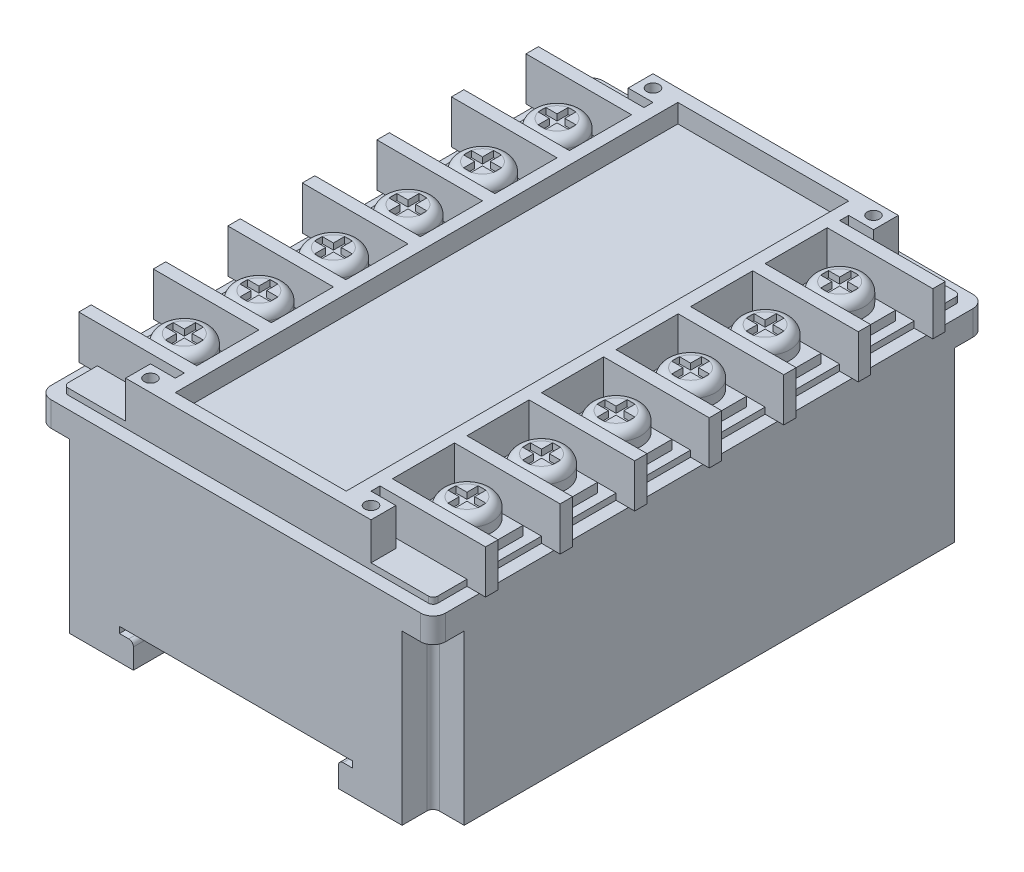
SolidWorks part; units mm, degrees
ref_plane "Front Plane" through (0, 0, 0) normal (0, 0, 1) x (1, 0, 0)
ref_plane "Top Plane" through (0, 0, 0) normal (0, 1, 0) x (1, 0, 0)
ref_plane "Right Plane" through (0, 0, 0) normal (1, 0, 0) x (0, 0, -1)
sketch "din rail profile sketch" plane through (0, 0, 0) normal (0, 0, 1) x (1, 0, 0)
  line L0 (0, 0) -> (1.75, 0)
  line L1 (2.25, -0.5) -> (2.25, -7)
  line L2 (3.25, -8) -> (34.25, -8)
  line L3 (18.75, -5.5) -> (18.75, 6.0393) construction
  line L4 (35.25, -0.5) -> (35.25, -7)
  line L5 (37.5, 0) -> (35.75, 0)
  line L6 (0, 1) -> (2.25, 1)
  line L7 (3.25, 0) -> (3.25, -6.8)
  line L8 (3.45, -7) -> (34.05, -7)
  line L9 (34.25, 0) -> (34.25, -6.8)
  line L10 (37.5, 1) -> (35.25, 1)
  line L11 (37.5, 1) -> (37.5, 0)
  line L12 (0, 0) -> (0, 1)
  line L13 (3.25, -7) -> (34.25, -7) construction
  line L14 (3.25, 1) -> (3.25, -7) construction
  line L15 (34.25, 1) -> (34.25, -7) construction
  line L16 (37.5, 0) -> (35.25, 0) construction
  line L17 (35.25, 0) -> (35.25, -8) construction
  line L18 (0, 0) -> (2.25, 0) construction
  line L19 (2.25, 0) -> (2.25, -8) construction
  line L20 (2.25, -8) -> (35.25, -8) construction
  line L21 (37.5, 1) -> (34.25, 1) construction
  line L22 (0, 1) -> (3.25, 1) construction
  arc A0 (3.45, -7) -> (3.25, -6.8) centre (3.45, -6.8) cw
  arc A1 (34.05, -7) -> (34.25, -6.8) centre (34.05, -6.8) ccw
  arc A2 (35.75, 0) -> (35.25, -0.5) centre (35.75, -0.5) ccw
  arc A3 (1.75, 0) -> (2.25, -0.5) centre (1.75, -0.5) cw
  arc A4 (2.25, -7) -> (3.25, -8) centre (3.25, -7) ccw
  arc A5 (35.25, -7) -> (34.25, -8) centre (34.25, -7) cw
  arc A6 (35.25, 1) -> (34.25, 0) centre (35.25, 0) ccw
  arc A7 (2.25, 1) -> (3.25, 0) centre (2.25, 0) cw
  point P24 (35.25, 0)
  point P28 (2.25, 0)
  dimension "D5" = 0.2
  dimension "D6" = 0.5
  dimension "D7" = 1
  dimension "D8" = 1
  dimension "D9" = 1
  dimension "D10" = 1
  dimension "D1" = 8
  dimension "D2" = 16.5
  dimension "D3" = 2.25
  dimension "D4" = 1
sketch "Sketch2" plane through (0, 0, 0) normal (0, 0, 1) x (1, 0, 0)
  line L0 (0, 0) -> (1.5, 0)
  line L1 (2.25, -0.75) -> (2.25, -4)
  line L3 (2.25, -4) -> (-13, -4)
  line L4 (-13, -4) -> (-13, 28.1)
  line L5 (-13, 28.1) -> (50.5, 28.1)
  line L6 (18.75, -5.5) -> (18.75, 6.0393) construction
  line L7 (0, 0) -> (0, 1)
  line L8 (0, 1) -> (37.5, 1)
  line L9 (18.75, -8) -> (18.75, 17.2279) construction
  line L10 (3.25, -8) -> (34.25, -8) construction
  line L11 (50.5, -4) -> (50.5, 28.1)
  line L12 (35.25, -4) -> (50.5, -4)
  line L13 (35.25, -0.75) -> (35.25, -4)
  line L14 (37.5, 0) -> (36, 0)
  line L15 (37.5, 0) -> (37.5, 1)
  arc A0 (1.5, 0) -> (2.25, -0.75) centre (1.5, -0.75) cw
  arc A1 (36, 0) -> (35.25, -0.75) centre (36, -0.75) ccw
  point P13 (2.25, 0)
  point P22 (18.75, 28.1)
  point P29 (18.75, 1)
  dimension "D1" = 0.75
  dimension "D2" = 4
  dimension "D3" = 31.75
  dimension "D4" = 32.1
extrude "Boss-Extrude1" add sketch "Sketch2" along normal mid plane 88.9
sketch "Sketch3" plane through (0, -4, 0) normal (0, -1, 0) x (1, 0, 0)
  line L1 (-13, 44.45) -> (-8, 44.45)
  line L2 (-13, 44.45) -> (-13, 39.45)
  line L3 (-13, 39.45) -> (-8, 39.45)
  line L4 (-8, 44.45) -> (-8, 39.45)
  line L5 (50.5, 44.45) -> (45.5, 44.45)
  line L6 (50.5, 44.45) -> (50.5, 39.45)
  line L7 (50.5, 39.45) -> (45.5, 39.45)
  line L8 (45.5, 44.45) -> (45.5, 39.45)
  line L9 (-13, -44.45) -> (-8, -44.45)
  line L10 (-13, -44.45) -> (-13, -39.45)
  line L11 (-13, -39.45) -> (-8, -39.45)
  line L12 (-8, -44.45) -> (-8, -39.45)
  line L13 (50.5, -44.45) -> (45.5, -44.45)
  line L14 (50.5, -44.45) -> (50.5, -39.45)
  line L15 (50.5, -39.45) -> (45.5, -39.45)
  line L16 (45.5, -44.45) -> (45.5, -39.45)
  dimension "D1" = 5
  dimension "D2" = 5
  dimension "D3" = 5
  dimension "D4" = 5
  dimension "D5" = 5
  dimension "D6" = 5
  dimension "D7" = 5
  dimension "D8" = 5
extrude "Cut-Extrude1" cut sketch "Sketch3" against normal offset from surface (27.1 mm away) 5 up to face at (18.75, 28.1, 0)
fillet "Fillet1" radius 1 4 edges at (-8, 9.55, 39.45) (-8, 9.55, -39.45) (45.5, 9.55, -39.45) (45.5, 9.55, 39.45)
fillet "Fillet2" radius 2 4 edges at (50.5, 25.6, 44.45) (-13, 25.6, 44.45) (-13, 25.6, -44.45) (50.5, 25.6, -44.45)
sketch "Sketch4" plane through (0, 28.1, 0) normal (0, 1, 0) x (1, 0, 0)
  line L5 (-16.0674, 47.3537) -> (53.5607, 47.3537)
  line L6 (-16.0674, 47.3537) -> (-16.0674, -47.8676)
  line L7 (-16.0674, -47.8676) -> (53.5607, -47.8676)
  line L8 (-11, -42.45) -> (48.5, -42.45)
  line L9 (48.5, -42.45) -> (48.5, 42.45)
  line L10 (48.5, 42.45) -> (-11, 42.45)
  line L11 (-11, 42.45) -> (-11, -42.45)
  line L12 (-10.25, -42.45) -> (47.75, -42.45)
  line L13 (48.5, -41.7) -> (48.5, 41.7)
  line L14 (47.75, 42.45) -> (-10.25, 42.45)
  line L15 (-11, 41.7) -> (-11, -41.7)
  line L16 (53.5607, 47.3537) -> (53.5607, -47.8676)
  arc A4 (48.5, 41.7) -> (47.75, 42.45) centre (47.75, 41.7) ccw
  arc A5 (47.75, -42.45) -> (48.5, -41.7) centre (47.75, -41.7) ccw
  arc A6 (-10.25, -42.45) -> (-11, -41.7) centre (-10.25, -41.7) cw
  arc A7 (-10.25, 42.45) -> (-11, 41.7) centre (-10.25, 41.7) ccw
  dimension "D2" = 0.75
  dimension "D1" = 2
extrude "Cut-Extrude2" cut sketch "Sketch4" against normal blind 1
sketch "Sketch5" plane through (0, 28.1, 0) normal (0, 1, 0) x (1, 0, 0)
  line L0 (47.75, 42.45) -> (-10.25, 42.45) construction
  line L1 (3, 42.45) -> (34.5, 42.45)
  line L2 (3, 38.45) -> (3, -38.45)
  line L3 (3, -42.45) -> (34.5, -42.45)
  line L4 (34.5, 38.45) -> (34.5, -38.45)
  line L5 (-10.25, -42.45) -> (47.75, -42.45) construction
  line L6 (-11, 41.7) -> (-11, -41.7) construction
  line L7 (48.5, -41.7) -> (48.5, 41.7) construction
  line L8 (34.5, 38.45) -> (38.5, 38.45)
  line L9 (38.5, 38.45) -> (38.5, 42.45)
  line L10 (47.75, 42.45) -> (-10.25, 42.45) construction
  line L11 (38.5, 42.45) -> (34.5, 42.45)
  line L12 (34.5, -42.45) -> (38.5, -42.45)
  line L13 (38.5, -42.45) -> (38.5, -38.45)
  line L14 (38.5, -38.45) -> (34.5, -38.45)
  line L15 (3, -42.45) -> (-1, -42.45)
  line L16 (-10.25, -42.45) -> (47.75, -42.45) construction
  line L17 (-1, -42.45) -> (-1, -38.45)
  line L18 (-1, -38.45) -> (3, -38.45)
  line L19 (3, 42.45) -> (-1, 42.45)
  line L20 (-1, 42.45) -> (-1, 38.45)
  line L21 (-1, 38.45) -> (3, 38.45)
  circle A0 centre (1, 40.45) radius 1
  circle A1 centre (36.5, 40.45) radius 1
  circle A2 centre (36.5, -40.45) radius 1
  circle A3 centre (1, -40.45) radius 1
  point P36 (1, 38.45)
  point P37 (-1, 40.45)
  point P38 (36.5, 38.45)
  point P39 (-1, -40.45)
  dimension "D11" = 2
  dimension "D12" = 2
  dimension "D13" = 2
  dimension "D14" = 2
  dimension "D1" = 14
  dimension "D2" = 14
  dimension "D3" = 4
  dimension "D4" = 4
  dimension "D5" = 4
  dimension "D6" = 4
  dimension "D7" = 4
  dimension "D8" = 4
  dimension "D9" = 4
  dimension "D10" = 4
extrude "Boss-Extrude2" add sketch "Sketch5" along normal blind 6
sketch "Sketch7" plane through (0, 28.1, 0) normal (0, 1, 0) x (1, 0, 0)
  line L0 (34.5, -38.45) -> (34.5, 38.45) construction
  line L1 (34.5, -1) -> (51.5, -1)
  line L2 (34.5, -1) -> (34.5, 1)
  line L3 (34.5, 1) -> (51.5, 1)
  line L4 (51.5, -1) -> (51.5, 1)
  line L5 (34.5, -38.45) -> (34.5, 38.45) construction
  line L6 (34.5, 11) -> (51.5, 11)
  line L7 (34.5, 11) -> (34.5, 13)
  line L8 (34.5, 13) -> (51.5, 13)
  line L9 (51.5, 11) -> (51.5, 13)
  line L10 (34.5, 23) -> (51.5, 23)
  line L11 (34.5, 23) -> (34.5, 25)
  line L12 (34.5, 25) -> (51.5, 25)
  line L13 (51.5, 23) -> (51.5, 25)
  line L15 (34.5, 35) -> (51.5, 35)
  line L16 (34.5, 35) -> (34.5, 37)
  line L17 (34.5, 37) -> (51.5, 37)
  line L18 (51.5, 35) -> (51.5, 37)
  line L19 (34.5, -11) -> (51.5, -11)
  line L20 (34.5, -11) -> (34.5, -13)
  line L21 (34.5, -13) -> (51.5, -13)
  line L22 (51.5, -11) -> (51.5, -13)
  line L23 (34.5, -23) -> (51.5, -23)
  line L24 (34.5, -23) -> (34.5, -25)
  line L25 (34.5, -25) -> (51.5, -25)
  line L26 (51.5, -23) -> (51.5, -25)
  line L27 (34.5, -35) -> (51.5, -35)
  line L28 (34.5, -35) -> (34.5, -37)
  line L29 (34.5, -37) -> (51.5, -37)
  line L30 (51.5, -35) -> (51.5, -37)
  point P6 (51.5, 0)
  dimension "D1" = 17
  dimension "D2" = 2
  dimension "D3" = 2
  dimension "D4" = 2
  dimension "D5" = 2
  dimension "D6" = 2
  dimension "D7" = 2
  dimension "D8" = 2
  dimension "D9" = 10
  dimension "D10" = 10
  dimension "D11" = 10
  dimension "D12" = 10
  dimension "D13" = 10
  dimension "D14" = 10
extrude "Boss-Extrude3" add sketch "Sketch7" along normal up to surface and the other way up to surface
ref_plane "Mid_Plane" through (18.75, 0, 0) normal (1, 0, 0) x (0, 0, -1)
mirror "Mirror1" about plane through (18.75, 0, 0) normal (1, 0, 0) of "Boss-Extrude3"
sketch "Sketch8" plane through (0, 34.1, 0) normal (0, 1, 0) x (1, 0, 0)
  line L0 (-10.25, -42.45) -> (47.75, -42.45) construction
  line L1 (5, 40.45) -> (32.5, 40.45)
  line L2 (5, 40.45) -> (5, -40.45)
  line L3 (5, -40.45) -> (32.5, -40.45)
  line L4 (32.5, 40.45) -> (32.5, -40.45)
  line L5 (3, -1) -> (3, -11) construction
  line L6 (34.5, -11) -> (34.5, -1) construction
  line L7 (47.75, 42.45) -> (-10.25, 42.45) construction
  point P10 (18.75, 42.45)
  dimension "D1" = 2
  dimension "D2" = 2
  dimension "D3" = 2
  dimension "D4" = 2
extrude "Cut-Extrude3" cut sketch "Sketch8" against normal blind 3
sketch "Sketch9" plane through (0, 28.1, 0) normal (0, 1, 0) x (1, 0, 0)
  line L0 (-11, -25) -> (-11, -35) construction
  line L1 (-9.5, -26.5) -> (1.5, -26.5)
  line L2 (-9.5, -26.5) -> (-9.5, -33.5)
  line L3 (-9.5, -33.5) -> (1.5, -33.5)
  line L4 (1.5, -26.5) -> (1.5, -33.5)
  line L5 (3, -25) -> (-11, -25) construction
  line L6 (3, -25) -> (3, -35) construction
  line L7 (-14, -35) -> (3, -35) construction
  dimension "D1" = 1.5
  dimension "D2" = 1.5
  dimension "D3" = 1.5
  dimension "D4" = 1.5
extrude "Boss-Extrude4" add sketch "Sketch9" along normal blind 1.5
ref_plane "Plane2" through (0, 0, 30) normal (0, 0, 1) x (1, 0, 0)
sketch "Sketch10" plane through (0, 0, 30) normal (0, 0, 1) x (1, 0, 0)
  line L0 (-4, 32.6) -> (-4, 29.6)
  line L1 (-9.5, 29.6) -> (1.5, 29.6) construction
  line L3 (-4, 29.6) -> (0, 29.6)
  line L4 (-4, 32.6) -> (-1.5, 32.6)
  line L5 (0, 31.1) -> (0, 29.6)
  arc A0 (-1.5, 32.6) -> (0, 31.1) centre (-1.5, 31.1) cw
  point P4 (-4, 29.6)
  point P8 (0, 32.6)
  dimension "D4" = 1.5
  dimension "D1" = 3
  dimension "D2" = 4
  dimension "D3" = 4
revolve "Revolve1" add sketch "Sketch10" angle 360 about L0
sketch "Sketch12" plane through (0, 32.6, 0) normal (0, 1, 0) x (1, 0, 0)
  line L0 (-3.375, -29.375) -> (-1.5794, -29.375)
  line L1 (-4.625, -32.4206) -> (-3.375, -32.4206)
  line L2 (-4.625, -32.4206) -> (-4.625, -30.625)
  line L3 (-4.625, -27.5794) -> (-3.375, -27.5794)
  line L4 (-3.375, -32.4206) -> (-3.375, -30.625)
  line L5 (-4.625, -32.4206) -> (-3.375, -27.5794) construction
  line L6 (-4.625, -27.5794) -> (-3.375, -32.4206) construction
  line L7 (-6.4206, -30.625) -> (-4.625, -30.625)
  line L8 (-6.4206, -30.625) -> (-6.4206, -29.375)
  line L9 (-6.4206, -29.375) -> (-4.625, -29.375)
  line L10 (-1.5794, -30.625) -> (-1.5794, -29.375)
  line L11 (-6.4206, -30.625) -> (-1.5794, -29.375) construction
  line L12 (-6.4206, -29.375) -> (-1.5794, -30.625) construction
  line L13 (-3.375, -29.375) -> (-3.375, -27.5794)
  line L14 (-3.375, -30.625) -> (-1.5794, -30.625)
  line L15 (-4.625, -29.375) -> (-4.625, -27.5794)
  circle A0 centre (-4, -30) radius 2.5 construction
  point P0 (-4, -30)
  point P8 (-4, -30)
  dimension "D1" = 1.25
  dimension "D2" = 1.25
extrude "Cut-Extrude4" cut sketch "Sketch12" against normal blind 1
pattern_linear "LPattern1" count 6 spacing 12 along (0, 0, -1) count 2 spacing 45.5 along (1, 0, 0) of "Boss-Extrude4", "Revolve1", "Cut-Extrude4"
equation "\"D2@Sketch3\"=\"D1@Sketch3\""
equation "\"D3@Sketch3\"=\"D1@Sketch3\""
equation "\"D4@Sketch3\"=\"D1@Sketch3\""
equation "\"D5@Sketch3\"=\"D1@Sketch3\""
equation "\"D6@Sketch3\"=\"D1@Sketch3\""
equation "\"D7@Sketch3\"=\"D1@Sketch3\""
equation "\"D8@Sketch3\"=\"D1@Sketch3\""
equation "\"D4@Sketch5\"=\"D3@Sketch5\""
equation "\"D5@Sketch5\"=\"D3@Sketch5\""
equation "\"D3@Sketch5\"=\"D6@Sketch5\""
equation "\"D8@Sketch5\"=\"D7@Sketch5\""
equation "\"D9@Sketch5\"=\"D7@Sketch5\""
equation "\"D10@Sketch5\"=\"D7@Sketch5\""
equation "\"D12@Sketch5\"=\"D11@Sketch5\""
equation "\"D13@Sketch5\"=\"D11@Sketch5\""
equation "\"D14@Sketch5\"=\"D11@Sketch5\""
equation "\"D10@Sketch7\"=\"D9@Sketch7\""
equation "\"D11@Sketch7\"=\"D9@Sketch7\""
equation "\"D12@Sketch7\"=\"D9@Sketch7\""
equation "\"D13@Sketch7\"=\"D9@Sketch7\""
equation "\"D14@Sketch7\"=\"D9@Sketch7\""
